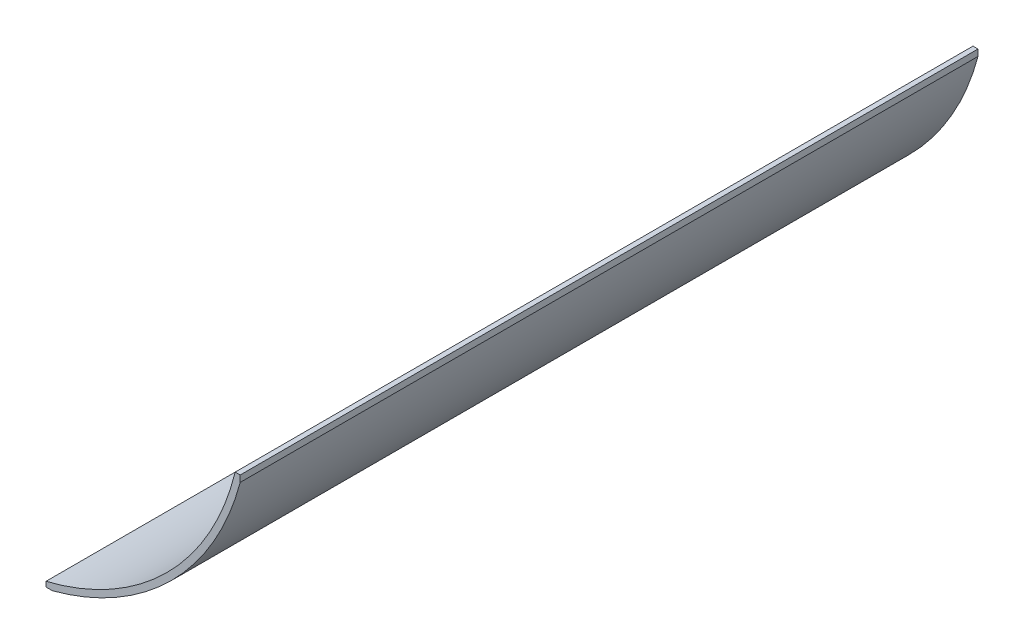
SolidWorks part; units mm, degrees
ref_plane "Спереди" through (0, 0, 0) normal (0, 0, 1) x (1, 0, 0)
ref_plane "Сверху" through (0, 0, 0) normal (0, 1, 0) x (1, 0, 0)
ref_plane "Справа" through (0, 0, 0) normal (1, 0, 0) x (0, 0, -1)
ref_plane "Плоскость4" through (0, 0, 111.5) normal (0, 0, 1) x (1, 0, 0)
sketch "Эскиз1" plane through (0, 0, 111.5) normal (0, 0, 1) x (1, 0, 0)
  line L0 (9.5, -38.8555) -> (9.5, -39.6327)
  line L1 (9.5, -39.6327) -> (10.5, -39.6327)
  line L2 (39.6327, -10.5) -> (39.6327, -9.5)
  line L3 (39.6327, -9.5) -> (38.8555, -9.5)
  arc A0 (38.8555, -9.5) -> (9.5, -38.8555) centre (0, 0) cw
  arc A1 (10.5, -39.6327) -> (39.6327, -10.5) centre (0, 0) ccw
extrude "Бобышка-Вытянуть1" add sketch "Эскиз1" against normal blind 114.5
